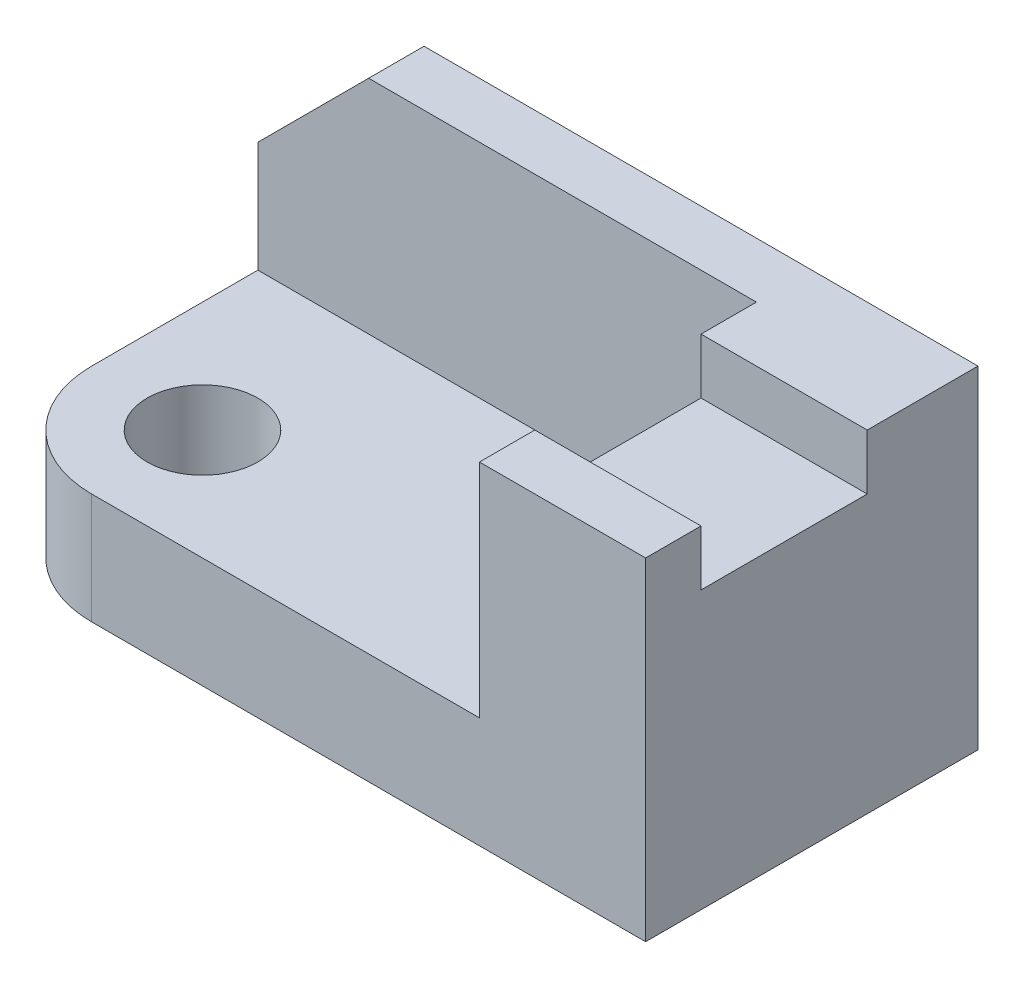
SolidWorks part; units mm, degrees
ref_plane "Front Plane" through (0, 0, 0) normal (0, 0, 1) x (1, 0, 0)
ref_plane "Top Plane" through (0, 0, 0) normal (0, 1, 0) x (1, 0, 0)
ref_plane "Right Plane" through (0, 0, 0) normal (1, 0, 0) x (0, 0, -1)
sketch "Sketch1" plane through (0, 0, 0) normal (0, 1, 0) x (1, 0, 0)
  line L1 (0, 0) -> (-120, 0)
  line L2 (0, 0) -> (0, 60)
  line L3 (0, 60) -> (-120, 60)
  line L4 (-120, 0) -> (-120, 60)
  dimension "D1" = 120
  dimension "D2" = 60
extrude "Boss-Extrude1" add sketch "Sketch1" along normal blind 20
sketch "Sketch2" plane through (0, 20, 0) normal (0, 1, 0) x (1, 0, 0)
  line L0 (-120, 0) -> (0, 0) construction
  line L1 (0, 60) -> (-30, 60)
  line L2 (0, 60) -> (0, 0)
  line L3 (0, 0) -> (-30, 0)
  line L4 (-30, 50) -> (-30, 0)
  line L6 (-120, 60) -> (-30, 60)
  line L7 (-120, 60) -> (-120, 50)
  line L8 (-120, 50) -> (-30, 50)
  point P14 (-183.8035, -83.953)
  dimension "D1" = 30
  dimension "D2" = 10
extrude "Boss-Extrude4" add sketch "Sketch2" along normal blind 40 contours L1 L6 L7 L8 L4 L3 L2
fillet "Fillet2" radius 20 1 edges at (-120, 10, 0)
chamfer "Chamfer1" distance 20 angle 45 1 edges at (-120, 60, -55)
sketch "Sketch5" plane through (0, 60, 0) normal (0, 1, 0) x (1, 0, 0)
  line L0 (-30, 50) -> (-30, 0) construction
  line L1 (-30, 40) -> (0, 40)
  line L2 (-30, 40) -> (-30, 10)
  line L3 (-30, 10) -> (0, 10)
  line L4 (0, 40) -> (0, 10)
  line L5 (0, 60) -> (0, 0) construction
  line L6 (-120, 50) -> (-30, 50) construction
  line L7 (-100, 0) -> (-30, 0) construction
  dimension "D1" = 10
  dimension "D2" = 10
extrude "Cut-Extrude1" cut sketch "Sketch5" against normal blind 10 contours L2 L1 L4 L3
sketch "Sketch6" plane through (0, 20, 0) normal (0, 1, 0) x (1, 0, 0)
  circle A0 centre (-100, 20) radius 10
extrude "Cut-Extrude2" cut sketch "Sketch6" against normal through all
